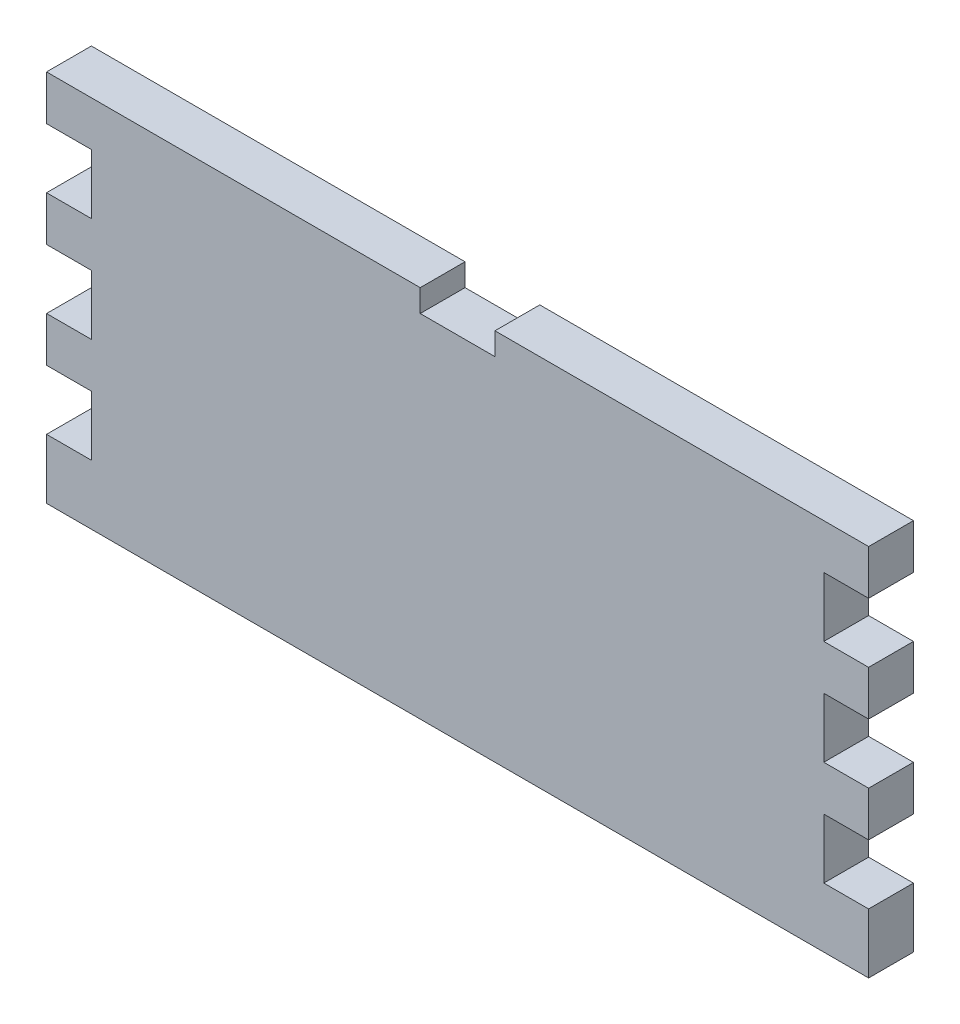
SolidWorks part; units mm, degrees
ref_plane "Plan de face" through (0, 0, 0) normal (0, 0, 1) x (1, 0, 0)
ref_plane "Plan de dessus" through (0, 0, 0) normal (0, 1, 0) x (1, 0, 0)
ref_plane "Plan de droite" through (0, 0, 0) normal (1, 0, 0) x (0, 0, -1)
sketch "Sketch1" plane through (0, 0, 0) normal (0, 0, 1) x (1, 0, 0)
  line L1 (-27.5, -12.5) -> (27.5, -12.5)
  line L2 (-27.5, -12.5) -> (-27.5, 12.5)
  line L3 (-27.5, 12.5) -> (27.5, 12.5)
  line L4 (27.5, -12.5) -> (27.5, 12.5)
  line L5 (-27.5, -12.5) -> (27.5, 12.5) construction
  line L6 (-27.5, 12.5) -> (27.5, -12.5) construction
  point P0 (0, 0)
  dimension "D1" = 55
  dimension "D2" = 25
extrude "Boss-Extrude1" add sketch "Sketch1" along normal blind 3
sketch "Sketch2" plane through (0, 0, 3) normal (0, 0, 1) x (1, 0, 0)
  line L0 (27.5, 12.5) -> (-27.5, 12.5) construction
  line L1 (-2.5, 12.5) -> (2.5, 12.5)
  line L2 (-2.5, 12.5) -> (-2.5, 11)
  line L3 (-2.5, 11) -> (2.5, 11)
  line L4 (2.5, 12.5) -> (2.5, 11)
  line L5 (-27.5, 12.5) -> (-27.5, -12.5) construction
  dimension "D1" = 1.5
  dimension "D2" = 5
  dimension "D3" = 25
extrude "Cut-Extrude1" cut sketch "Sketch2" against normal blind 3
sketch "Sketch3" plane through (0, 0, 3) normal (0, 0, 1) x (1, 0, 0)
  line L0 (-27.5, 12.5) -> (-27.5, -12.5) construction
  line L1 (-27.5, 9.5) -> (-24.5, 9.5)
  line L2 (-27.5, 9.5) -> (-27.5, 5.5)
  line L3 (-27.5, 5.5) -> (-24.5, 5.5)
  line L4 (-24.5, 9.5) -> (-24.5, 5.5)
  line L5 (-2.5, 12.5) -> (-27.5, 12.5) construction
  line L7 (-27.5, 2.5) -> (-24.5, 2.5)
  line L8 (-27.5, 2.5) -> (-27.5, -1.5)
  line L9 (-27.5, -1.5) -> (-24.5, -1.5)
  line L10 (-24.5, 2.5) -> (-24.5, -1.5)
  line L11 (-27.5, -4.5) -> (-24.5, -4.5)
  line L12 (-27.5, -4.5) -> (-27.5, -8.5)
  line L13 (-27.5, -8.5) -> (-24.5, -8.5)
  line L14 (-24.5, -4.5) -> (-24.5, -8.5)
  dimension "D1" = 4
  dimension "D2" = 3
  dimension "D3" = 3
  dimension "D4" = 3
  dimension "D5" = 4
  dimension "D6" = 3
  dimension "D7" = 4
  dimension "D8" = 3
extrude "Cut-Extrude2" cut sketch "Sketch3" against normal blind 3
sketch "Sketch4" plane through (0, 0, 3) normal (0, 0, 1) x (1, 0, 0)
  line L0 (27.5, -12.5) -> (27.5, 12.5) construction
  line L1 (27.5, 9.5) -> (24.5, 9.5)
  line L2 (27.5, 9.5) -> (27.5, 5.5)
  line L3 (27.5, 5.5) -> (24.5, 5.5)
  line L4 (24.5, 9.5) -> (24.5, 5.5)
  line L5 (27.5, 12.5) -> (2.5, 12.5) construction
  line L7 (27.5, 2.5) -> (24.5, 2.5)
  line L8 (27.5, 2.5) -> (27.5, -1.5)
  line L9 (27.5, -1.5) -> (24.5, -1.5)
  line L10 (24.5, 2.5) -> (24.5, -1.5)
  line L11 (27.5, -4.5) -> (24.5, -4.5)
  line L12 (27.5, -4.5) -> (27.5, -8.5)
  line L13 (27.5, -8.5) -> (24.5, -8.5)
  line L14 (24.5, -4.5) -> (24.5, -8.5)
  dimension "D1" = 3
  dimension "D2" = 3
  dimension "D3" = 4
  dimension "D4" = 4
  dimension "D5" = 3
  dimension "D6" = 3
  dimension "D7" = 4
  dimension "D8" = 3
  dimension "D9" = 3
extrude "Cut-Extrude3" cut sketch "Sketch4" against normal blind 3
